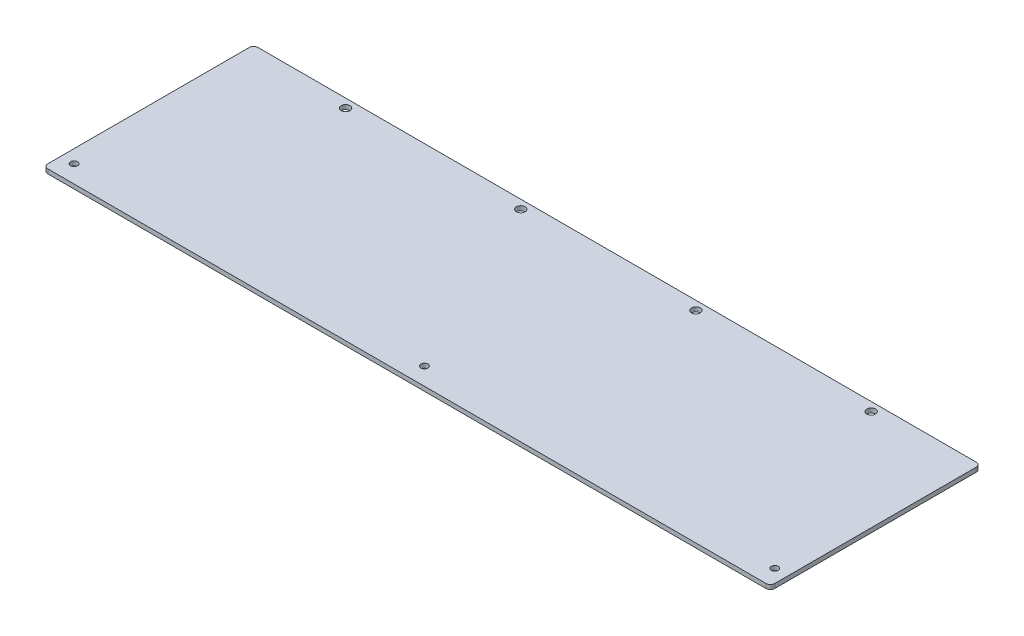
SolidWorks part; units mm, degrees
material "PC High Viscosity"
ref_plane "Front Plane" through (0, 0, 0) normal (0, 0, 1) x (1, 0, 0)
ref_plane "Top Plane" through (0, 0, 0) normal (0, 1, 0) x (1, 0, 0)
ref_plane "Right Plane" through (0, 0, 0) normal (1, 0, 0) x (0, 0, -1)
sketch "Sketch1" plane through (0, 0, 0) normal (0, 1, 0) x (1, 0, 0)
  line L1 (-263.525, 76.2) -> (263.525, 76.2)
  line L2 (-263.525, 76.2) -> (-263.525, -76.2)
  line L3 (-263.525, -76.2) -> (263.525, -76.2)
  line L4 (263.525, 76.2) -> (263.525, -76.2)
  line L5 (-263.525, 76.2) -> (263.525, -76.2) construction
  line L6 (-263.525, -76.2) -> (263.525, 76.2) construction
  point P0 (0, 0)
  point P6 (0, -63.5)
  point P10 (25.4, -63.5)
  point P11 (50.8, -63.5)
  point P12 (76.2, -63.5)
  point P13 (101.6, -63.5)
  point P14 (127, -63.5)
  point P15 (152.4, -63.5)
  point P16 (177.8, -63.5)
  point P17 (203.2, -63.5)
  point P18 (228.6, -63.5)
  point P19 (254, -63.5)
  point P20 (0, -63.5)
  point P21 (25.4, -63.5)
  point P22 (50.8, -63.5)
  point P23 (76.2, -63.5)
  point P24 (101.6, -63.5)
  point P25 (127, -63.5)
  point P26 (152.4, -63.5)
  point P27 (177.8, -63.5)
  point P28 (203.2, -63.5)
  point P29 (228.6, -63.5)
  point P30 (-25.4, -63.5)
  point P31 (0, -63.5)
  point P32 (25.4, -63.5)
  point P33 (50.8, -63.5)
  point P34 (76.2, -63.5)
  point P35 (101.6, -63.5)
  point P36 (127, -63.5)
  point P37 (152.4, -63.5)
  point P38 (177.8, -63.5)
  point P39 (203.2, -63.5)
  point P40 (-50.8, -63.5)
  point P41 (-25.4, -63.5)
  point P42 (0, -63.5)
  point P43 (25.4, -63.5)
  point P44 (50.8, -63.5)
  point P45 (76.2, -63.5)
  point P46 (101.6, -63.5)
  point P47 (127, -63.5)
  point P48 (152.4, -63.5)
  point P49 (177.8, -63.5)
  point P50 (-76.2, -63.5)
  point P51 (-50.8, -63.5)
  point P52 (-25.4, -63.5)
  point P53 (0, -63.5)
  point P54 (25.4, -63.5)
  point P55 (50.8, -63.5)
  point P56 (76.2, -63.5)
  point P57 (101.6, -63.5)
  point P58 (127, -63.5)
  point P59 (152.4, -63.5)
  point P60 (-101.6, -63.5)
  point P61 (-76.2, -63.5)
  point P62 (-50.8, -63.5)
  point P63 (-25.4, -63.5)
  point P64 (0, -63.5)
  point P65 (25.4, -63.5)
  point P66 (50.8, -63.5)
  point P67 (76.2, -63.5)
  point P68 (101.6, -63.5)
  point P69 (127, -63.5)
  point P70 (-127, -63.5)
  point P71 (-101.6, -63.5)
  point P72 (-76.2, -63.5)
  point P73 (-50.8, -63.5)
  point P74 (-25.4, -63.5)
  point P75 (0, -63.5)
  point P76 (25.4, -63.5)
  point P77 (50.8, -63.5)
  point P78 (76.2, -63.5)
  point P79 (101.6, -63.5)
  point P80 (-152.4, -63.5)
  point P81 (-127, -63.5)
  point P82 (-101.6, -63.5)
  point P83 (-76.2, -63.5)
  point P84 (-50.8, -63.5)
  point P85 (-25.4, -63.5)
  point P86 (0, -63.5)
  point P87 (25.4, -63.5)
  point P88 (50.8, -63.5)
  point P89 (76.2, -63.5)
  point P90 (-177.8, -63.5)
  point P91 (-152.4, -63.5)
  point P92 (-127, -63.5)
  point P93 (-101.6, -63.5)
  point P94 (-76.2, -63.5)
  point P95 (-50.8, -63.5)
  point P96 (-25.4, -63.5)
  point P97 (0, -63.5)
  point P98 (25.4, -63.5)
  point P99 (50.8, -63.5)
  point P100 (-203.2, -63.5)
  point P101 (-177.8, -63.5)
  point P102 (-152.4, -63.5)
  point P103 (-127, -63.5)
  point P104 (-101.6, -63.5)
  point P105 (-76.2, -63.5)
  point P106 (-50.8, -63.5)
  point P107 (-25.4, -63.5)
  point P108 (0, -63.5)
  point P109 (25.4, -63.5)
  point P110 (-228.6, -63.5)
  point P111 (-203.2, -63.5)
  point P112 (-177.8, -63.5)
  point P113 (-152.4, -63.5)
  point P114 (-127, -63.5)
  point P115 (-101.6, -63.5)
  point P116 (-76.2, -63.5)
  point P117 (-50.8, -63.5)
  point P118 (-25.4, -63.5)
  point P119 (0, -63.5)
  point P120 (-25.4, -63.5)
  point P121 (-50.8, -63.5)
  point P122 (-76.2, -63.5)
  point P123 (-101.6, -63.5)
  point P124 (-127, -63.5)
  point P125 (-152.4, -63.5)
  point P126 (-177.8, -63.5)
  point P127 (-203.2, -63.5)
  point P128 (-228.6, -63.5)
  point P129 (-254, -63.5)
  dimension "D1" = 152.4
  dimension "D2" = 527.05
  dimension "D3" = 12.7
  dimension "D6" = 25.4
  dimension "D7" = 25.4
  dimension "D4" = 11
  dimension "D5" = 11
extrude "Boss-Extrude1" add sketch "Sketch1" along normal blind 3.175
hole_wizard "#7 (0.201) Diameter Hole1" positions "Sketch2" profile "Sketch3" hole size "#7" standard "ANSI Inch" end condition through all
sketch "Sketch2" plane through (0, 0, 0) normal (0, -1, 0) x (-1, 0, 0)
  point P0 (-254, -63.5)
  point P30 (0, -63.5)
  point P60 (254, -63.5)
sketch "Sketch3" plane through (254, 0, 63.5) normal (1, 0, 0) x (0, 0, -1)
  line L0 (0, 0) -> (0, 3.175)
  line L1 (0, 3.175) -> (2.5527, 3.175)
  line L2 (2.5527, 3.175) -> (2.5527, 0)
  line L5 (2.5527, 0) -> (0, 0)
  line L11 (0, -6.35) -> (0, 107.95) construction
  dimension "Thru Hole Dia." = 5.1054
  dimension "Thru Hole Depth" = 3.175
fillet "Fillet1" radius 3.175 4 edges at (-263.525, 1.5875, 76.2) (-263.525, 1.5875, -76.2) (263.525, 1.5875, 76.2) (263.525, 1.5875, -76.2)
hole_wizard "1/4 (0.25) Diameter Hole1" positions "Sketch4" profile "Sketch5" hole size "1/4" standard "ANSI Inch" end condition through all
sketch "Sketch4" plane through (0, 3.175, 0) normal (0, 1, 0) x (1, 0, 0)
  line L0 (260.35, 76.2) -> (-260.35, 76.2) construction
  point P0 (190.5, 69.85)
  point P2 (63.5, 69.85)
  point P4 (-63.5, 69.85)
  point P6 (-190.5, 69.85)
  dimension "D1" = 127
  dimension "D2" = 127
  dimension "D3" = 127
  dimension "D4" = 63.5
  dimension "D5" = 6.35
sketch "Sketch5" plane through (190.5, 3.175, -69.85) normal (1, 0, 0) x (0, 0, 1)
  line L0 (0, 0) -> (0, 3.175)
  line L1 (0, 3.175) -> (3.175, 3.175)
  line L2 (3.175, 3.175) -> (3.175, 0)
  line L5 (3.175, 0) -> (0, 0)
  line L11 (0, -6.35) -> (0, 107.95) construction
  dimension "Thru Hole Dia." = 6.35
  dimension "Thru Hole Depth" = 3.175
